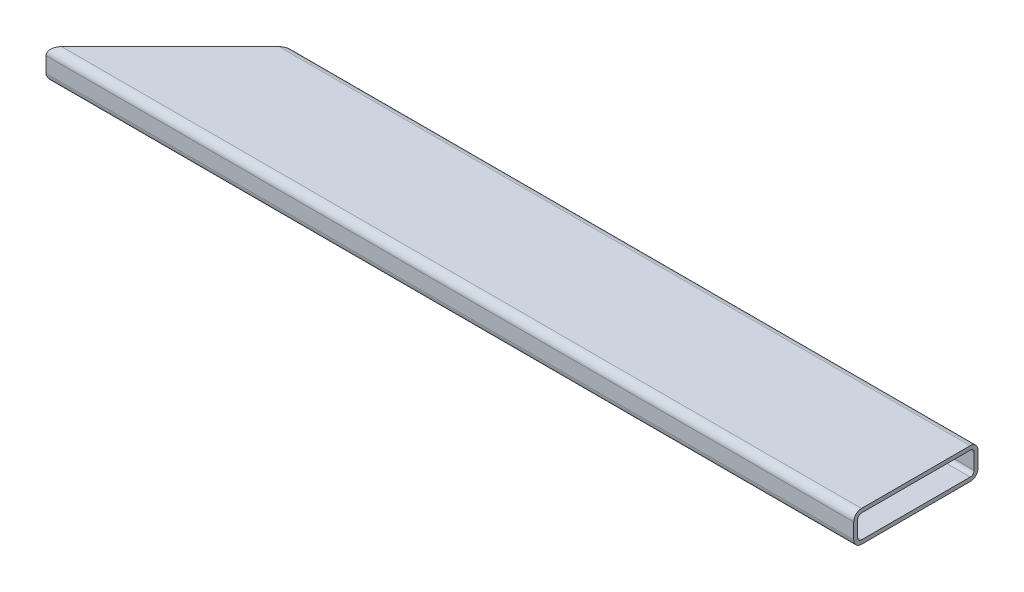
SolidWorks part; units mm, degrees
material "Alloy Steel"
ref_plane "Front Plane" through (0, 0, 0) normal (0, 0, 1) x (1, 0, 0)
ref_plane "Top Plane" through (0, 0, 0) normal (0, 1, 0) x (1, 0, 0)
ref_plane "Right Plane" through (0, 0, 0) normal (1, 0, 0) x (0, 0, -1)
sketch "Sketch1" plane through (0, 0, 0) normal (1, 0, 0) x (0, 0, -1)
  line L1 (0, 0) -> (101.6, 0)
  line L2 (0, 0) -> (0, 25.4)
  line L3 (0, 25.4) -> (101.6, 25.4)
  line L4 (101.6, 0) -> (101.6, 25.4)
  dimension "D1" = 25.4
  dimension "D2" = 101.6
extrude "Boss-Extrude1" add sketch "Sketch1" along normal blind 660.4
fillet "Fillet1" radius 6.35
shell "Shell1" thickness 3.175
sketch "Sketch2" plane through (0, 25.4, 0) normal (0, 1, 0) x (1, 0, 0)
  line L0 (0, 0) -> (101.6, 101.6)
  line L1 (0, 101.6) -> (660.4, 101.6) construction
  line L2 (101.6, 101.6) -> (0, 101.6)
  line L3 (0, 101.6) -> (0, 0)
  line L4 (660.4, 0) -> (0, 0) construction
  dimension "D1" = 45
extrude "Cut-Extrude1" cut sketch "Sketch2" against normal blind 25.4
